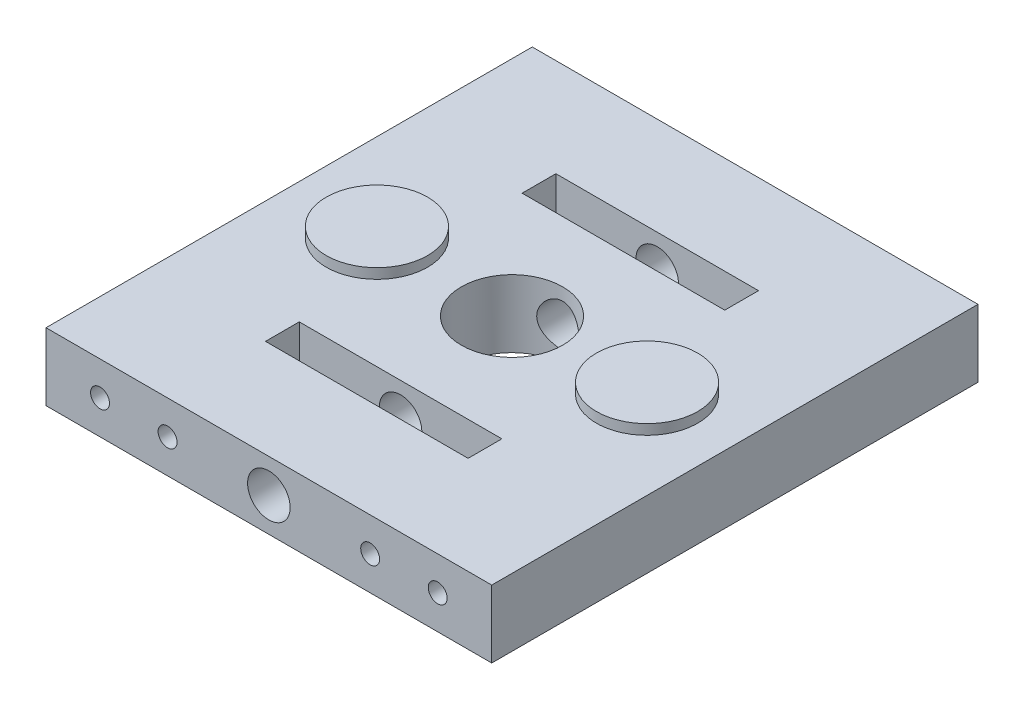
SolidWorks part; units mm, degrees
ref_plane "Front Plane" through (0, 0, 0) normal (0, 0, 1) x (1, 0, 0)
ref_plane "Top Plane" through (0, 0, 0) normal (0, 1, 0) x (1, 0, 0)
ref_plane "Right Plane" through (0, 0, 0) normal (1, 0, 0) x (0, 0, -1)
sketch "Sketch1" plane through (0, 0, 0) normal (0, 1, 0) x (1, 0, 0)
  line L1 (-33, -36) -> (33, -36)
  line L2 (-33, -36) -> (-33, 36)
  line L3 (-33, 36) -> (33, 36)
  line L4 (33, -36) -> (33, 36)
  line L5 (-33, -36) -> (33, 36) construction
  line L6 (-33, 36) -> (33, -36) construction
  point P0 (0, 0)
  dimension "D1" = 72
  dimension "D2" = 66
extrude "Boss-Extrude1" add sketch "Sketch1" along normal blind 10
sketch "Sketch2" plane through (0, 0, 36) normal (0, 0, 1) x (1, 0, 0)
  line L0 (-15, 5) -> (-25, 5) construction
  line L1 (25.4779, 5.6572) -> (25, 5) construction
  line L2 (25, 5) -> (15, 5) construction
  line L3 (-25, 5) -> (25, 5) construction
  line L4 (-33, 0) -> (33, 0) construction
  circle A0 centre (-15, 5) radius 1.4
  circle A1 centre (15, 5) radius 1.4
  circle A3 centre (-25, 5) radius 1.4
  circle A4 centre (25, 5) radius 1.4
  point P9 (0, 5)
  dimension "D1" = 2.8
  dimension "D2" = 50
  dimension "D3" = 10
  dimension "D4" = 5
extrude "Cut-Extrude1" cut sketch "Sketch2" against normal blind 10
mirror "Mirror1" about plane through (0, 0, 0) normal (0, 0, 1) of "Cut-Extrude1"
sketch "Sketch3" plane through (0, 10, 0) normal (0, 1, 0) x (1, 0, 0)
  line L0 (0, 19) -> (0, 0) construction
  line L1 (-15, -21.5) -> (15, -21.5)
  line L2 (-15, -21.5) -> (-15, -16.5)
  line L3 (-15, -16.5) -> (15, -16.5)
  line L4 (15, -21.5) -> (15, -16.5)
  line L5 (-15, -21.5) -> (15, -16.5) construction
  line L6 (-15, -16.5) -> (15, -21.5) construction
  line L7 (-15, 16.5) -> (15, 16.5)
  line L8 (-15, 16.5) -> (-15, 21.5)
  line L9 (-15, 21.5) -> (15, 21.5)
  line L10 (15, 16.5) -> (15, 21.5)
  line L11 (-15, 16.5) -> (15, 21.5) construction
  line L12 (-15, 21.5) -> (15, 16.5) construction
  line L13 (0, 0) -> (0, -19) construction
  point P0 (0, -19)
  point P5 (0, 19)
  dimension "D1" = 5
  dimension "D2" = 30
  dimension "D5" = 19
extrude "Cut-Extrude2" cut sketch "Sketch3" against normal through all both
sketch "Sketch4" plane through (0, 0, 36) normal (0, 0, 1) x (1, 0, 0)
  line L0 (-15, 5) -> (15, 5) construction
  circle A0 centre (0, 5) radius 3.15
  dimension "D1" = 6.3
extrude "Cut-Extrude3" cut sketch "Sketch4" against normal through all both
sketch "Sketch5" plane through (0, 10, 0) normal (0, 1, 0) x (1, 0, 0)
  line L0 (-20, 0) -> (20, 0) construction
  circle A0 centre (-20, 0) radius 7.5
  circle A1 centre (20, 0) radius 7.5
  point P3 (0, 0)
  dimension "D1" = 15
  dimension "D2" = 20
extrude "Boss-Extrude2" add sketch "Sketch5" along normal blind 1.5
sketch "Sketch6" plane through (0, 10, 0) normal (0, 1, 0) x (1, 0, 0)
  circle A0 centre (0, 0) radius 7.5
  dimension "D1" = 15
extrude "Cut-Extrude4" cut sketch "Sketch6" against normal through all both and the other way through all
